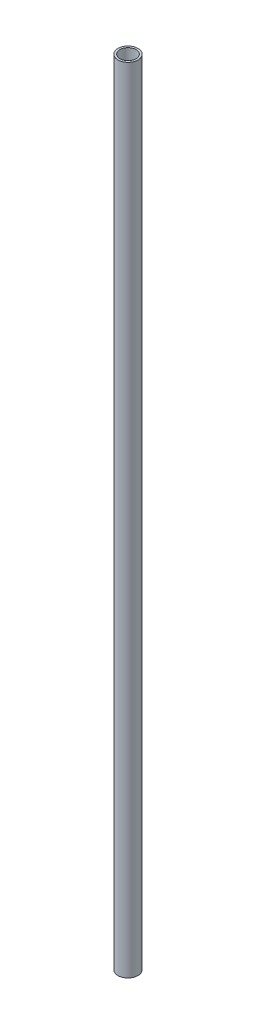
SolidWorks part; units mm, degrees
material "Hexcel AS4C (3000 丝)"
ref_plane "前视基准面" through (0, 0, 0) normal (0, 0, 1) x (1, 0, 0)
ref_plane "上视基准面" through (0, 0, 0) normal (0, 1, 0) x (1, 0, 0)
ref_plane "右视基准面" through (0, 0, 0) normal (1, 0, 0) x (0, 0, -1)
sketch "草图1" plane through (0, 0, 0) normal (0, 1, 0) x (1, 0, 0)
  circle A0 centre (0, 0) radius 10
  circle A1 centre (0, 0) radius 8
  dimension "D1" = 20
  dimension "D2" = 16
extrude "凸台-拉伸1" add sketch "草图1" along normal blind 791.6
